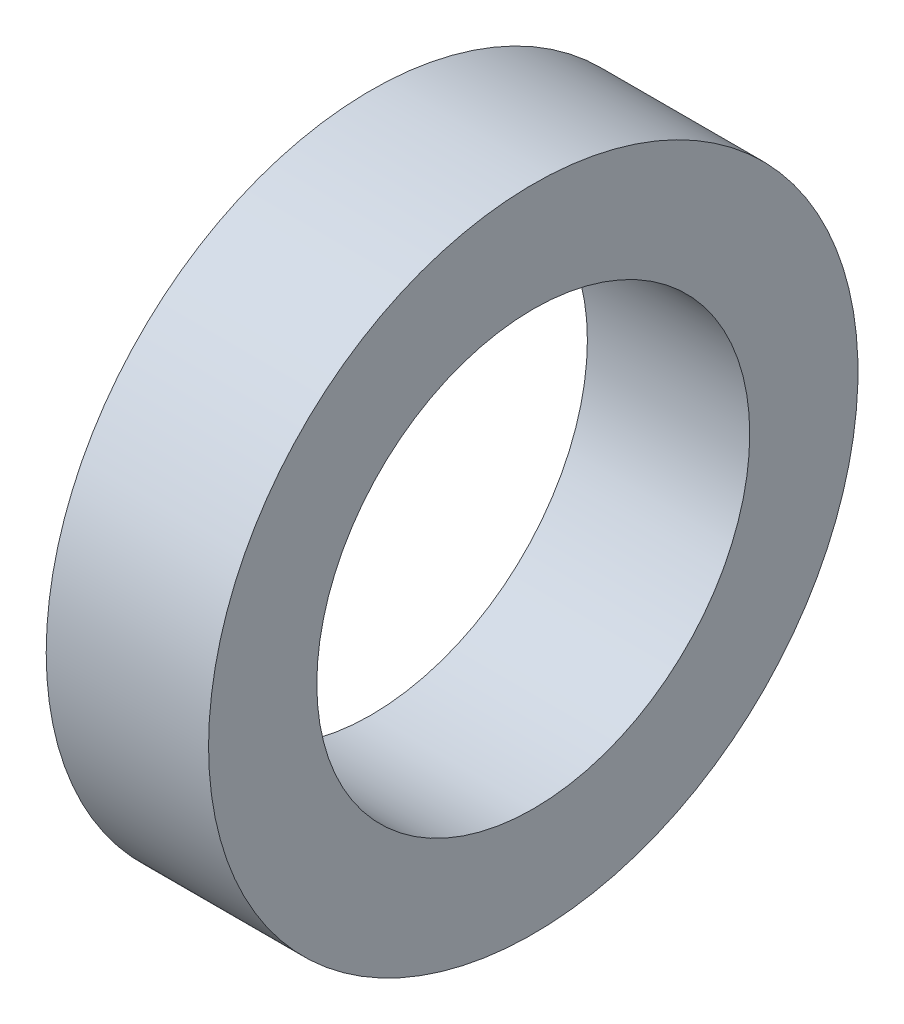
SolidWorks part; units mm, degrees
ref_plane "Plane1" through (0, 0, 0) normal (0, 0, 1) x (1, 0, 0)
ref_plane "Plane2" through (0, 0, 0) normal (0, 1, 0) x (1, 0, 0)
ref_plane "Plane3" through (0, 0, 0) normal (1, 0, 0) x (0, 0, -1)
sketch "Esquisse1" plane through (0, 0, 0) normal (0, 0, 1) x (1, 0, 0)
  line L0 (0, 0) -> (-3, 0)
  line L1 (0, 0) -> (0, 2)
  line L2 (-3, 2) -> (0, 2)
  line L3 (-3, 2) -> (-3, 0)
  dimension "D1" = 3
  dimension "D2" = 2
sketch "Esquisse2" plane through (0, 0, 0) normal (1, 0, 0) x (0, 0, -1)
  circle A0 centre (0, -4) radius 4
  dimension "D1" = 8
sweep "joint" add profiles "Esquisse1" path "Esquisse2"
